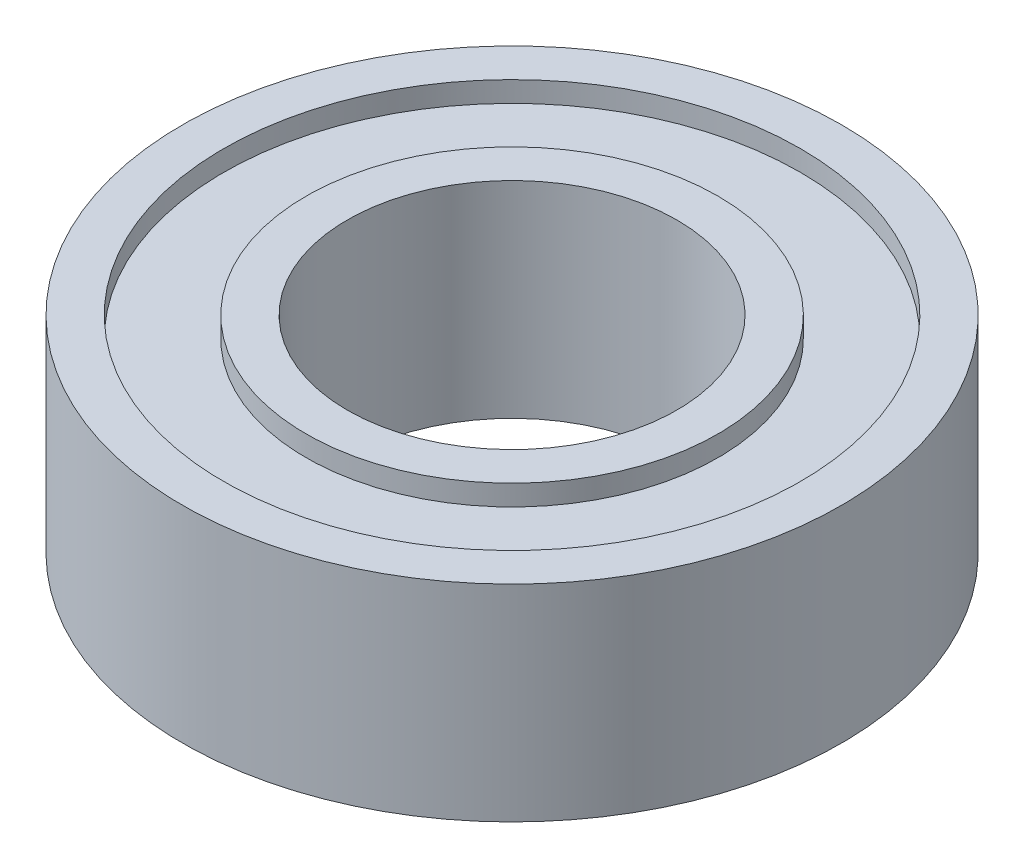
SolidWorks part; units mm, degrees
ref_plane "Plan de face" through (0, 0, 0) normal (0, 0, 1) x (1, 0, 0)
ref_plane "Plan de dessus" through (0, 0, 0) normal (0, 1, 0) x (1, 0, 0)
ref_plane "Plan de droite" through (0, 0, 0) normal (1, 0, 0) x (0, 0, -1)
sketch "Esquisse1" plane through (0, 0, 0) normal (0, 0, 1) x (1, 0, 0)
  line L0 (7, 2.5) -> (8, 2.5)
  line L1 (4, 2.5) -> (5, 2.5)
  line L2 (4, 2.5) -> (4, -2.5)
  line L3 (4, -2.5) -> (5, -2.5)
  line L4 (8, 2.5) -> (8, -2.5)
  line L5 (7, -2.5) -> (8, -2.5)
  line L6 (5, 2.5) -> (5, 2)
  line L7 (5, 2) -> (7, 2)
  line L8 (7, 2.5) -> (7, 2)
  line L9 (0, -3.9841) -> (0, 8.8488)
  line L10 (5, -2.5) -> (5, -2)
  line L11 (5, -2) -> (7, -2)
  line L12 (7, -2.5) -> (7, -2)
  dimension "D1" = 5
  dimension "D2" = 4
  dimension "D3" = 2.5
  dimension "D4" = 8
  dimension "D5" = 1
  dimension "D6" = 1
  dimension "D7" = 0.5
  dimension "D8" = 0.5
  dimension "D9" = 2
  dimension "D10" = 1
revolve "Révolution1" add sketch "Esquisse1" angle 360 about L9
